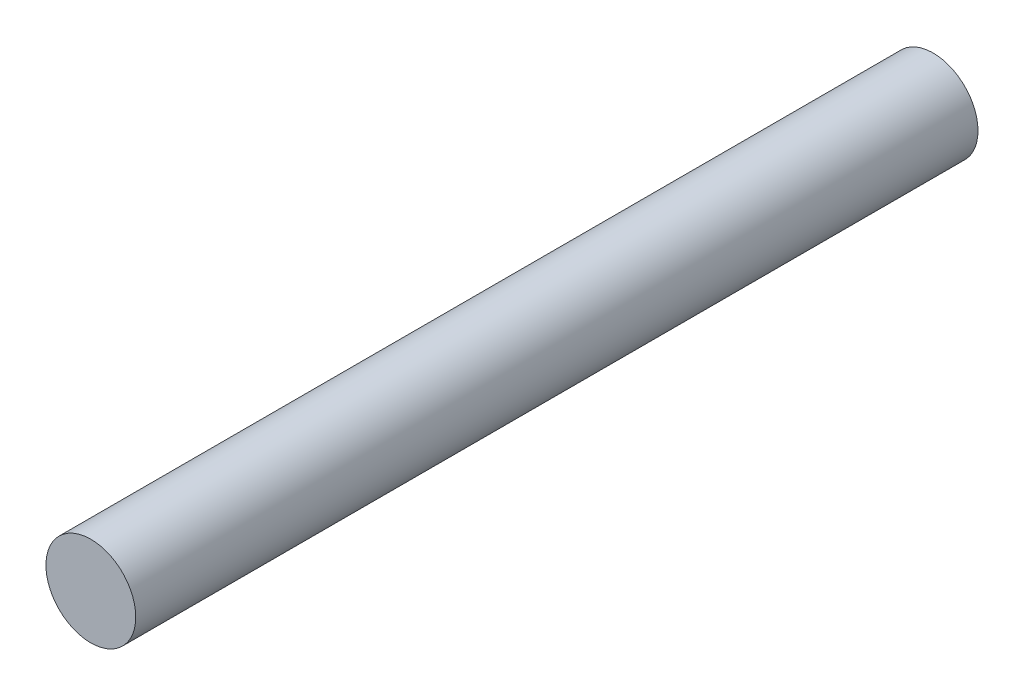
SolidWorks part; units mm, degrees
ref_plane "Front Plane" through (0, 0, 0) normal (0, 0, 1) x (1, 0, 0)
ref_plane "Top Plane" through (0, 0, 0) normal (0, 1, 0) x (1, 0, 0)
ref_plane "Right Plane" through (0, 0, 0) normal (1, 0, 0) x (0, 0, -1)
sketch "Sketch1" plane through (0, 0, 0) normal (0, 0, 1) x (1, 0, 0)
  circle A0 centre (0, 0) radius 8
  dimension "D1" = 16
extrude "Boss-Extrude1" add sketch "Sketch1" along normal blind 150
